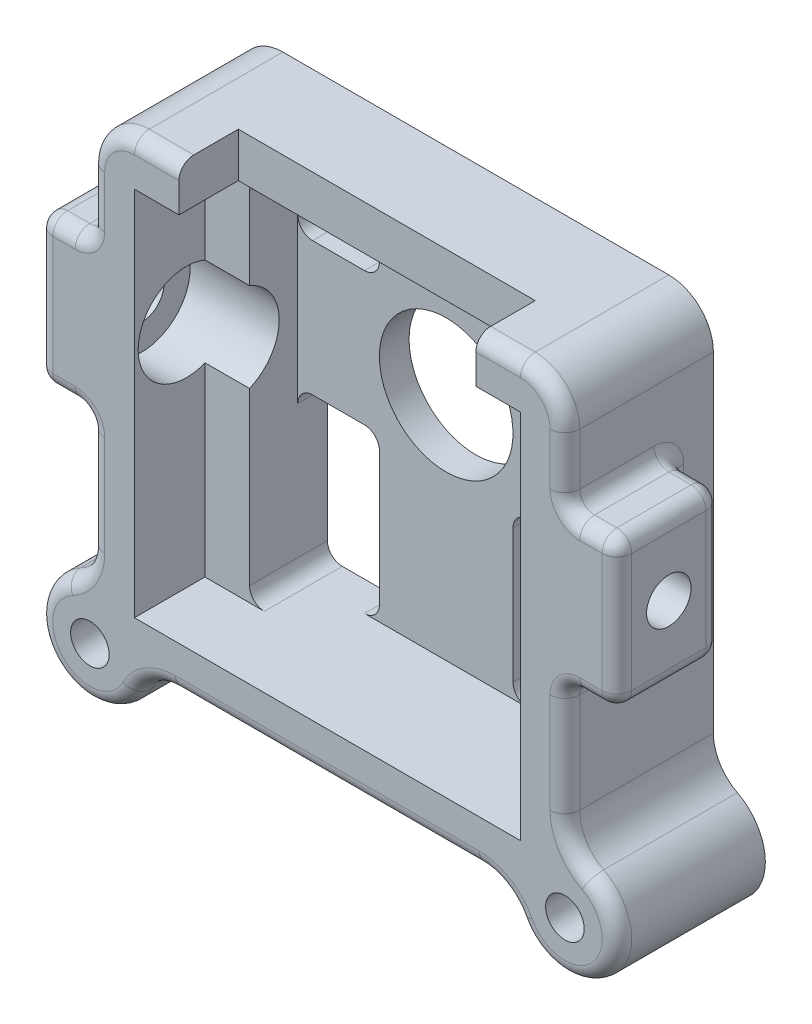
SolidWorks part; units mm, degrees
ref_plane "前基準面" through (0, 0, 0) normal (0, 0, 1) x (1, 0, 0)
ref_plane "上基準面" through (0, 0, 0) normal (0, 1, 0) x (1, 0, 0)
ref_plane "右基準面" through (0, 0, 0) normal (1, 0, 0) x (0, 0, -1)
sketch "草圖1" plane through (0, 0, 0) normal (0, 0, 1) x (1, 0, 0)
  line L0 (-16, 15.5) -> (16, 15.5)
  line L1 (-13, -12.5) -> (13, -12.5)
  line L2 (-13, -12.5) -> (-13, 12.5)
  line L3 (-13, 12.5) -> (13, 12.5)
  line L4 (13, -12.5) -> (13, 12.5)
  line L5 (-13, -12.5) -> (13, 12.5) construction
  line L6 (-13, 12.5) -> (13, -12.5) construction
  line L7 (16, -15.5) -> (16, 15.5)
  line L8 (-16, -15.5) -> (16, -15.5)
  line L9 (-16, -15.5) -> (-16, 15.5)
  point P0 (0, 0)
  dimension "D1" = 25
  dimension "D2" = 26
  dimension "D3" = 3
extrude "填料-伸長1" add sketch "草圖1" against normal blind 10
sketch "草圖2" plane through (0, 0, -10) normal (0, 0, -1) x (-1, 0, 0)
  line L0 (-4.5, 12.5) -> (-4.5, -12.5)
  line L1 (-13, 12.5) -> (13, 12.5) construction
  line L2 (13, -12.5) -> (-13, -12.5) construction
  line L3 (4.5, 12.5) -> (4.5, -12.5)
  line L4 (-4.5, 12.5) -> (4.5, 12.5)
  line L5 (-4.5, -12.5) -> (4.5, -12.5)
  line L6 (13, 12.5) -> (13, -12.5) construction
  line L7 (-13, -1.5) -> (13, -1.5)
  line L8 (-13, -1.5) -> (-13, 7.5)
  line L9 (-13, 7.5) -> (13, 7.5)
  line L10 (13, -1.5) -> (13, 7.5)
  line L11 (-13, -1.5) -> (13, 7.5) construction
  line L12 (-13, 7.5) -> (13, -1.5) construction
  circle A0 centre (0, 3) radius 4.5
  point P17 (0, 0)
  point P18 (0, 0)
  point P19 (0, 0)
  point P20 (0, 0)
  point P21 (0, 0)
  point P22 (0, 0)
  line M10 (-13, -12.5) -> (-13, 12.5)
  line M11 (-13, 12.5) -> (13, 12.5)
  line M12 (13, 12.5) -> (13, -12.5)
  line M13 (13, -12.5) -> (-13, -12.5)
  dimension "D1" = 9
  dimension "D2" = 9.5
extrude "填料-伸長2" add sketch "草圖2" against normal blind 2 contours L9 L3 L7 M12 | A0 L3 L9 | A0 L7 L3 | A0 L0 L7 | A0 L9 L0 | L0 L9 L3 M11 | L9 L7 L0 M10 | L7 L0 L3 M13
sketch "草圖4" plane through (0, 0, -10) normal (0, 0, -1) x (-1, 0, 0)
  line L0 (-4.5, -12.5) -> (-13, -12.5) construction
  line L1 (-13, 12.5) -> (-10, 12.5)
  line L2 (-13, 12.5) -> (-13, -12.5)
  line L3 (-13, -12.5) -> (-10, -12.5)
  line L4 (-10, 12.5) -> (-10, -12.5)
  dimension "D1" = 3
extrude "填料-伸長3" add sketch "草圖4" against normal blind 5.25
mirror "鏡射1" about plane through (0, 0, 0) normal (1, 0, 0) of "填料-伸長3"
sketch "草圖5" plane through (16, 0, 0) normal (1, 0, 0) x (0, 0, -1)
  line L0 (8, 3) -> (10, 3) construction
  line L1 (0, 8) -> (7, 8)
  line L2 (0, 8) -> (0, -2)
  line L3 (0, -2) -> (7, -2)
  line L4 (7, 8) -> (7, -2)
  line L5 (0, 8) -> (7, -2) construction
  line L6 (0, -2) -> (7, 8) construction
  line L8 (0, -15.5) -> (0, 15.5) construction
  point P0 (3.5, 3)
  dimension "D1" = 10
  dimension "D2" = 7
extrude "填料-伸長4" add sketch "草圖5" along normal blind 3.5
hole_wizard "M3 六角承窩頭蓋螺釘的柱孔1" positions "草圖6" profile "草圖7" counterbore size "M3" standard "ISO"
sketch "草圖6" plane through (10, 0, 0) normal (-1, 0, 0) x (0, 0, 1)
  point P0 (-3.5, 3)
sketch "草圖7" plane through (10, 3, -3.5) normal (0, 1, 0) x (0, 0, 1)
  line L0 (0, 0) -> (0, 9.5)
  line L1 (0, 9.5) -> (1.5, 9.5)
  line L3 (1.5, 9.5) -> (1.5, 6)
  line L4 (1.5, 6) -> (3.25, 6)
  line L5 (3.25, 6) -> (3.25, 0)
  line L7 (3.25, 0) -> (0, 0)
  line L11 (0, -6.35) -> (0, 107.95) construction
  dimension "貫穿孔直徑" = 3
  dimension "貫穿孔深度" = 9.5
  dimension "柱孔直徑" = 6.5
  dimension "柱孔深度" = 6
mirror "鏡射2" about plane through (0, 0, 0) normal (1, 0, 0) of "M3 六角承窩頭蓋螺釘的柱孔1", "填料-伸長4"
sketch "草圖8" plane through (0, 15.5, 0) normal (0, 1, 0) x (1, 0, 0)
  line L0 (16, 0) -> (-16, 0) construction
  line L1 (10, 0) -> (-10, 0)
  line L2 (10, 0) -> (10, 4)
  line L3 (10, 4) -> (-10, 4)
  line L4 (-10, 0) -> (-10, 4)
  point P6 (0, 0)
  dimension "D1" = 4
  dimension "D2" = 20
extrude "除料-伸長1" cut sketch "草圖8" against normal up to surface (3 mm away) up to face at (0, 12.5, -6.25)
sketch "草圖11" plane through (0, 0, 0) normal (0, 0, 1) x (1, 0, 0)
  line L0 (16, -14) -> (16, -12)
  line L1 (14.5, -15.5) -> (12.5, -15.5)
  circle A0 centre (16, -15.5) radius 1.5
  circle A1 centre (16, -15.5) radius 3.5
  line M17 (-16, -15.5) -> (16, -15.5)
  line M18 (16, -15.5) -> (16, -2)
  dimension "D1" = 3
  dimension "D2" = 2
extrude "填料-伸長5" add sketch "草圖11" against normal up to surface (10 mm away) contours A1 A0 M17 M18
hole_wizard "Ø2.6 (2.6) 直徑孔1" positions "草圖12" profile "草圖13" hole size "Ø2.6" standard "ISO" end condition through all
sketch "草圖12" plane through (0, 0, 0) normal (0, 0, 1) x (1, 0, 0)
  point P0 (16, -15.5)
sketch "草圖13" plane through (16, -15.5, 0) normal (1, 0, 0) x (0, -1, 0)
  line L0 (0, 0) -> (0, 10)
  line L1 (0, 10) -> (1.3, 10)
  line L2 (1.3, 10) -> (1.3, 0)
  line L5 (1.3, 0) -> (0, 0)
  line L11 (0, -6.35) -> (0, 107.95) construction
  dimension "貫穿孔直徑" = 2.6
  dimension "貫穿孔深度" = 10
mirror "鏡射3" about plane through (0, 0, 0) normal (1, 0, 0) of "Ø2.6 (2.6) 直徑孔1", "填料-伸長5"
fillet "圓角1" radius 3 6 edges at (16, 15.5, -5) (-16, 15.5, -5) (16, -12, -5) (12.5, -15.5, -5) (-12.5, -15.5, -5) (-16, -12, -5)
fillet "圓角2" radius 1 53 edges at (-4.5, 12.5, -9) (10, 12.5, -7.375) (10, -1.5, -9) (-4.5, -1.5, -9) (-10, -1.5, -9) (4.5, -1.5, -9) (4.5, 12.5, -9) (-10, 12.5, -7.375) (-10, 7.5, -9) (-4.5, 7.5, -9) (10, 7.5, -9) (4.5, 7.5, -9) (4.5, -12.5, -9) (10, -12.5, -7.375) (-4.5, -12.5, -9) (-10, -12.5, -7.375) (0, -15.5, 0) (11.7903, -15.9354, 0) (-11.7903, -15.9354, 0) (11.5, 15.5, 0) (18.4749, -17.9749, 0) (-18.4749, -17.9749, 0) (-11.5, 15.5, 0) (15.1213, 14.6213, 0) (16.4354, -11.2903, 0) (-16.4354, -11.2903, 0) (-15.1213, 14.6213, 0) (16, 10.25, 0) (16, -5.8669, 0) (-16, -5.8669, 0) (-16, 10.25, 0) (17.75, 8, 0) (19.5, 8, -3.5) (16, 8, -3.5) (17.75, -2, 0) (17.75, 8, -7) (19.5, 3, -7) (16, 3, -7) (17.75, -2, -7) (16, -2, -3.5) (19.5, -2, -3.5) (-19.5, 3, -7) (-19.5, 3, 0) (-19.5, 8, -3.5) (-19.5, -2, -3.5) (-17.75, -2, 0) (-17.75, -2, -7) (-17.75, 8, -7) (-17.75, 8, 0) (-16, -2, -3.5) (-16, 8, -3.5) (-16, 3, -7) (19.5, 3, 0)
